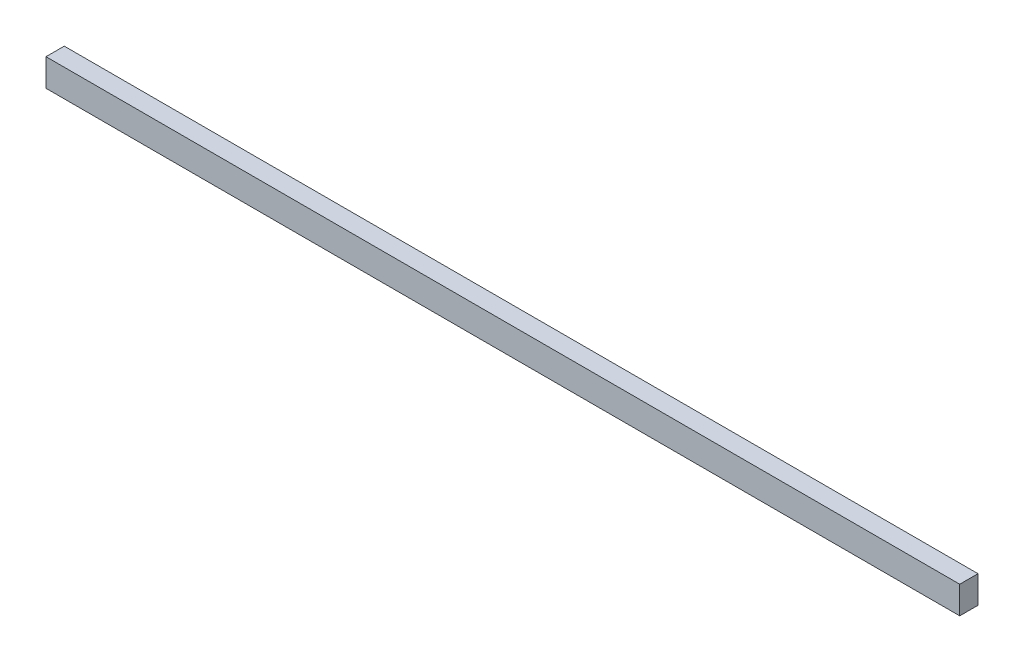
SolidWorks part; units mm, degrees
material "普通碳钢"
ref_plane "前视基准面" through (0, 0, 0) normal (0, 0, 1) x (1, 0, 0)
ref_plane "上视基准面" through (0, 0, 0) normal (0, 1, 0) x (1, 0, 0)
ref_plane "右视基准面" through (0, 0, 0) normal (1, 0, 0) x (0, 0, -1)
sketch "草图2" plane through (0, 0, 0) normal (1, 0, 0) x (0, 0, -1)
  line L1 (-0.01, 0.015) -> (0.01, 0.015)
  line L2 (-0.01, 0.015) -> (-0.01, -0.015)
  line L3 (-0.01, -0.015) -> (0.01, -0.015)
  line L4 (0.01, 0.015) -> (0.01, -0.015)
  line L5 (-0.01, 0.015) -> (0.01, -0.015) construction
  line L6 (-0.01, -0.015) -> (0.01, 0.015) construction
  point P0 (0, 0)
extrude "凸台-拉伸2" add sketch "草图2" along normal blind 1
